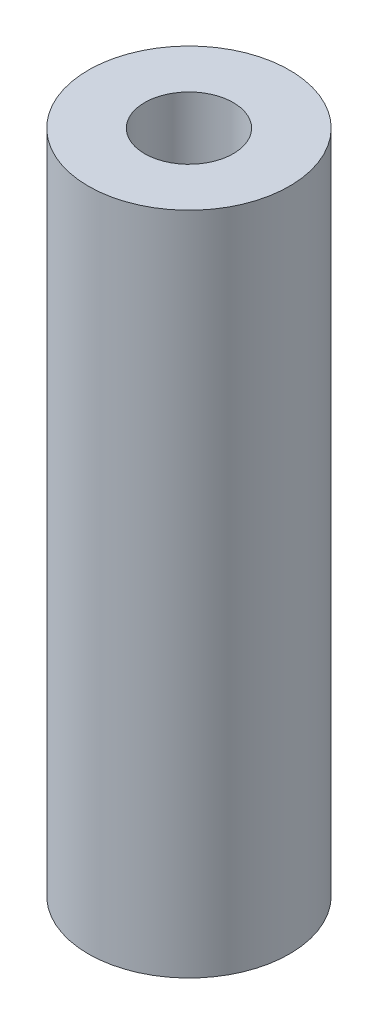
SolidWorks part; units mm, degrees
ref_plane "Front Plane" through (0, 0, 0) normal (0, 0, 1) x (1, 0, 0)
ref_plane "Top Plane" through (0, 0, 0) normal (0, 1, 0) x (1, 0, 0)
ref_plane "Right Plane" through (0, 0, 0) normal (1, 0, 0) x (0, 0, -1)
sketch "Sketch1" plane through (0, 0, 0) normal (0, 1, 0) x (1, 0, 0)
  circle A0 centre (0, 0) radius 5.9
  dimension "D1" = 11.8
extrude "Boss-Extrude1" add sketch "Sketch1" along normal blind 39
sketch "Sketch2" plane through (0, 39, 0) normal (0, 1, 0) x (1, 0, 0)
  circle A0 centre (0, 0) radius 2.6
  dimension "D1" = 5.2
extrude "Cut-Extrude1" cut sketch "Sketch2" against normal blind 4
